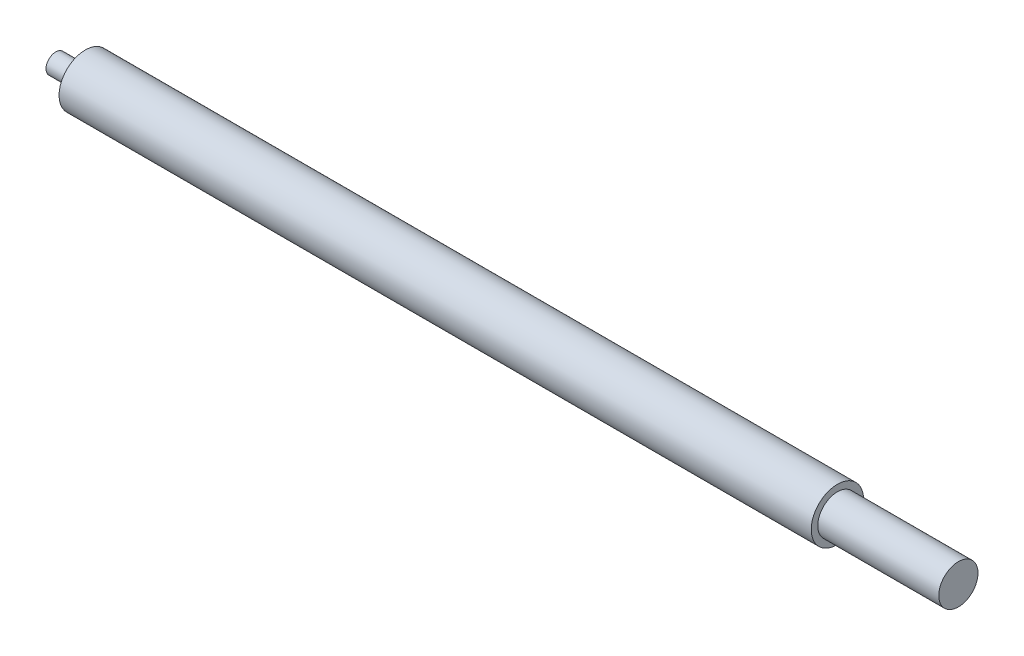
SolidWorks part; units mm, degrees
ref_plane "前视基准面" through (0, 0, 0) normal (0, 0, 1) x (1, 0, 0)
ref_plane "上视基准面" through (0, 0, 0) normal (0, 1, 0) x (1, 0, 0)
ref_plane "右视基准面" through (0, 0, 0) normal (1, 0, 0) x (0, 0, -1)
sketch "草图1" plane through (0, 0, 0) normal (1, 0, 0) x (0, 0, -1)
  circle A0 centre (0, 0) radius 8
  dimension "D1" = 16
extrude "凸台-拉伸1" add sketch "草图1" along normal mid plane 230
sketch "草图2" plane through (115, 0, 0) normal (1, 0, 0) x (0, 0, -1)
  circle A0 centre (0, 0) radius 6
  dimension "D1" = 12
extrude "凸台-拉伸2" add sketch "草图2" along normal blind 37
sketch "草图3" plane through (152, 0, 0) normal (1, 0, 0) x (0, 0, -1)
  circle A0 centre (0, 0) radius 5
  dimension "D1" = 10
sketch "草图5" plane through (-115, 0, 0) normal (-1, 0, 0) x (0, 0, 1)
  circle A1 centre (0, 0) radius 3
extrude "凸台-拉伸4" add sketch "草图5" along normal mid plane 18
